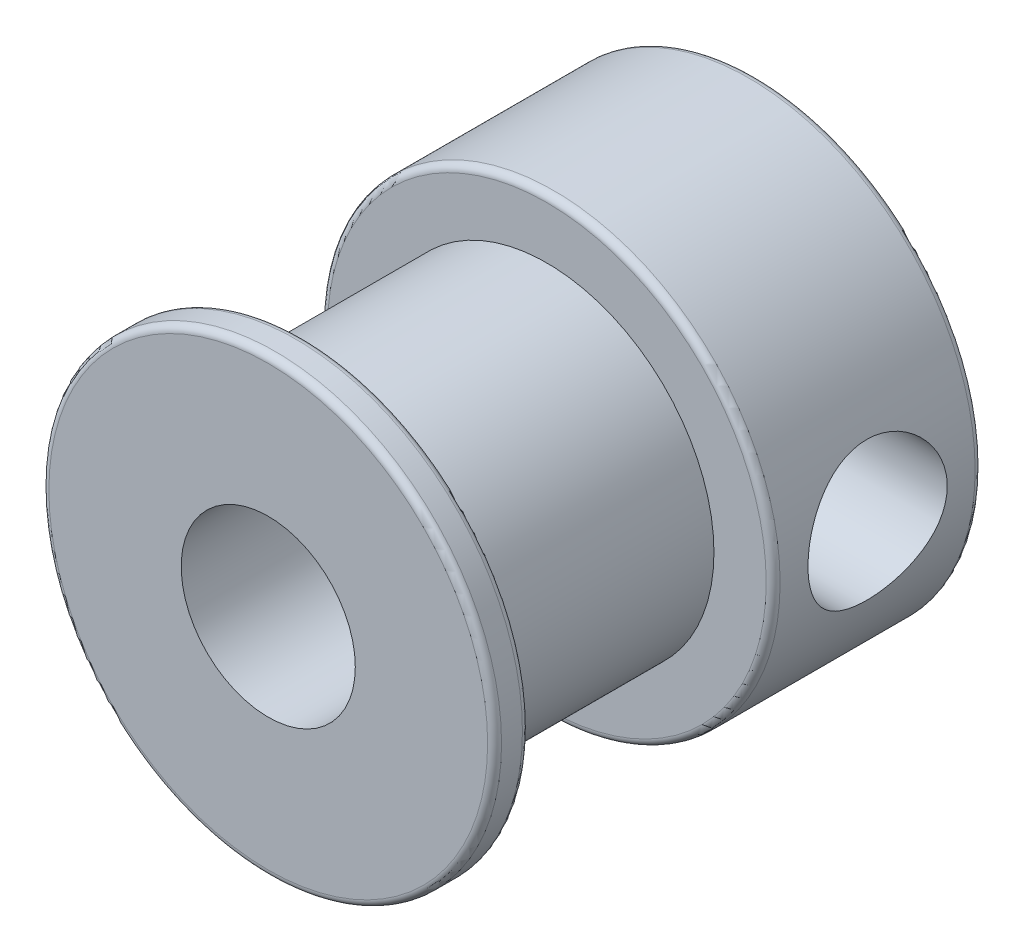
SolidWorks part; units mm, degrees
ref_plane "Ön Düzlem" through (0, 0, 0) normal (0, 0, 1) x (1, 0, 0)
ref_plane "Üst Düzlem" through (0, 0, 0) normal (0, 1, 0) x (1, 0, 0)
ref_plane "Sağ Düzlem" through (0, 0, 0) normal (1, 0, 0) x (0, 0, -1)
sketch "Sketch1" plane through (0, 0, 0) normal (0, 0, 1) x (1, 0, 0)
  circle A0 centre (0, 0) radius 6.5
  circle A1 centre (0, 0) radius 2.5
  dimension "D1" = 13
  dimension "D2" = 5
extrude "Boss-Extrude1" add sketch "Sketch1" along normal blind 14
sketch "Sketch2" plane through (0, 0, 0) normal (1, 0, 0) x (0, 0, -1)
  line L1 (-13, -9.2161) -> (-6, -9.2161)
  line L2 (-13, -9.2161) -> (-13, -4.8)
  line L3 (-13, -4.8) -> (-6, -4.8)
  line L4 (-6, -9.2161) -> (-6, -4.8)
  line L5 (-15.6439, 0) -> (2.3729, 0) construction
  line L6 (-14, 6.5) -> (-14, -6.5) construction
  dimension "D1" = 9.6
  dimension "D2" = 1
  dimension "D3" = 7
revolve "Cut-Revolve1" cut sketch "Sketch2" angle 360 about L5
fillet "Fillet2" radius 0.2 4 edges at (6.5, 0, 14) (6.5, 0, 13) (6.5, 0, 0) (-6.5, 0, 6)
ref_plane "Plane1" through (6.5, 0, 0) normal (1, 0, 0) x (0, 0, -1)
sketch "Sketch4" plane through (6.5, 0, 0) normal (1, 0, 0) x (0, 0, -1)
  line L0 (-0.2, 0) -> (-5.8, 0) construction
  line L1 (-0.2, 6.5) -> (-0.2, -6.5) construction
  line L2 (-5.8, 6.5) -> (-5.8, -6.5) construction
  circle A0 centre (-3, 0) radius 2
  point P8 (-3.7133, 0)
  point P9 (-3, 0)
  dimension "D1" = 4
extrude "Cut-Extrude1" cut sketch "Sketch4" against normal blind 6
